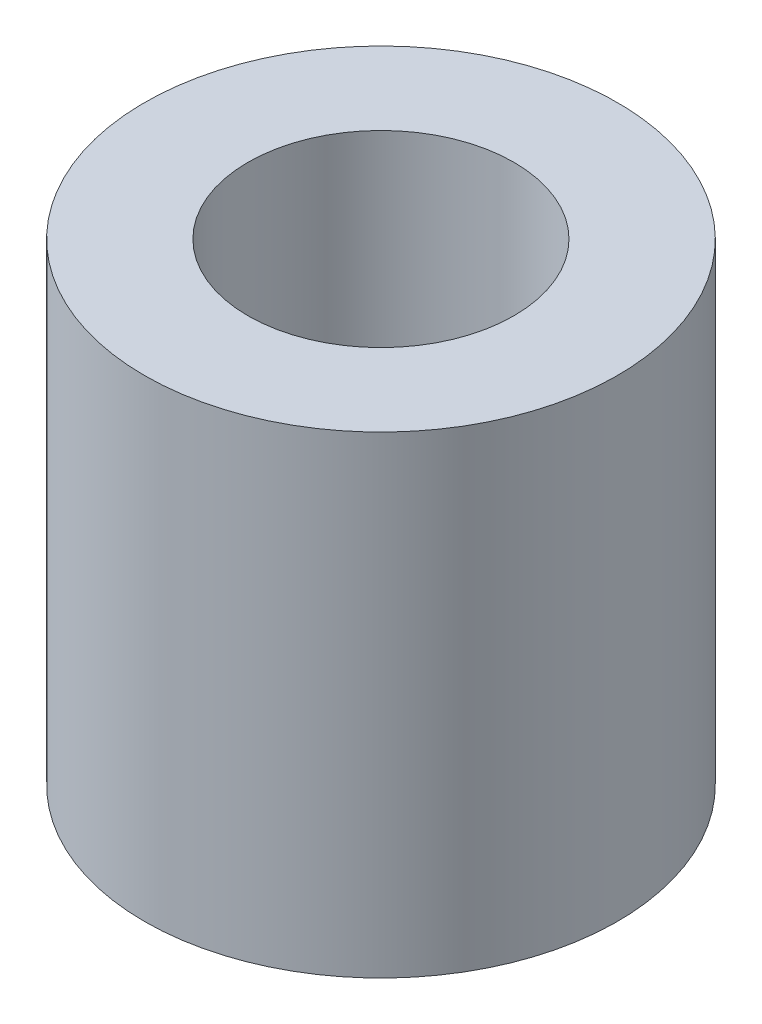
SolidWorks part; units mm, degrees
ref_plane "Front" through (0, 0, 0) normal (0, 0, 1) x (1, 0, 0)
ref_plane "Top" through (0, 0, 0) normal (0, 1, 0) x (1, 0, 0)
ref_plane "Right" through (0, 0, 0) normal (1, 0, 0) x (0, 0, -1)
sketch "Sketch1" plane through (0, 0, 0) normal (0, 1, 0) x (1, 0, 0)
  circle A0 centre (0, 0) radius 2.25
  circle A1 centre (0, 0) radius 4
  dimension "D1" = 4.5
extrude "Boss-Extrude1" add sketch "Sketch1" along normal blind 8
